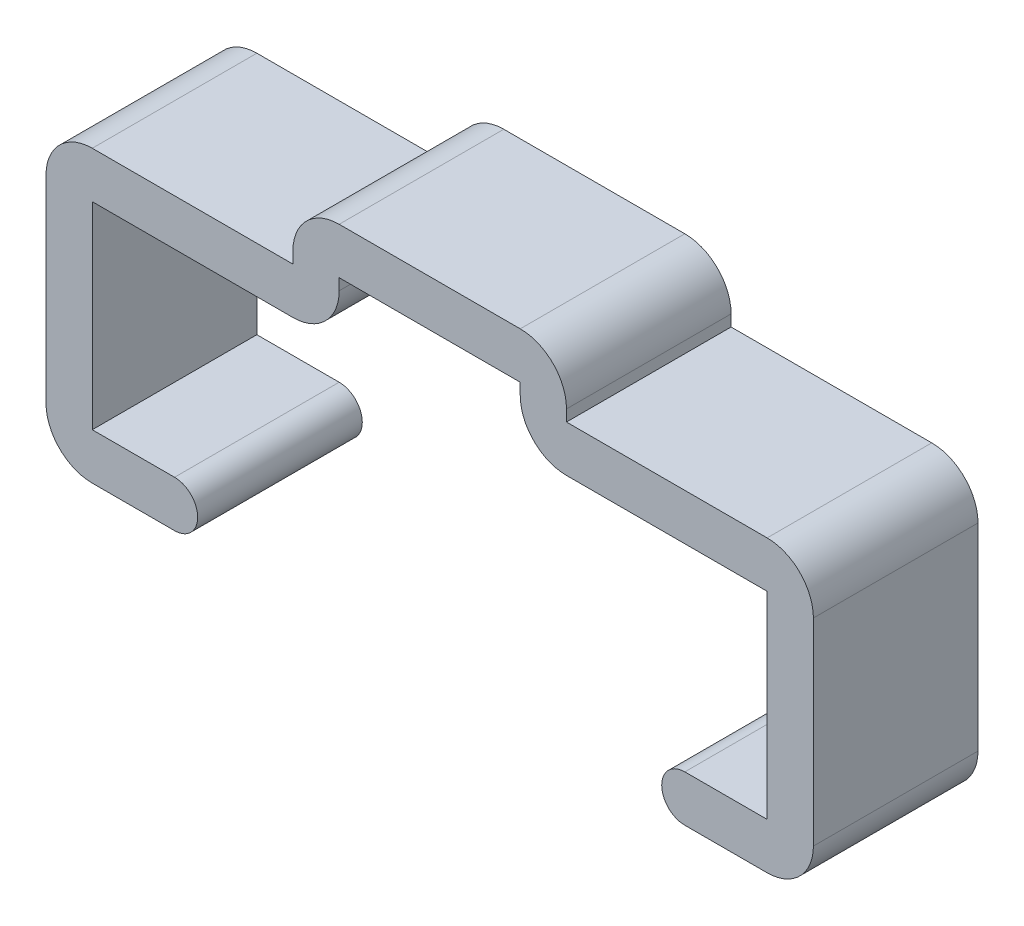
SolidWorks part; units mm, degrees
ref_plane "Front Plane" through (0, 0, 0) normal (0, 0, 1) x (1, 0, 0)
ref_plane "Top Plane" through (0, 0, 0) normal (0, 1, 0) x (1, 0, 0)
ref_plane "Right Plane" through (0, 0, 0) normal (1, 0, 0) x (0, 0, -1)
sketch "Sketch1" plane through (0, 0, 0) normal (0, 0, 1) x (1, 0, 0)
  line L0 (-20.5, -6) -> (-15.5, -6)
  line L1 (-20.5, 6) -> (-8.31, 6)
  line L2 (-20.5, 6) -> (-20.5, -6)
  line L4 (20.5, 6) -> (20.5, -6)
  line L5 (15.5, -6) -> (20.5, -6)
  line L6 (-20.5, -8.81) -> (-15.5, -8.81)
  line L7 (-5.5, 9.5) -> (5.5, 9.5)
  line L8 (-5.5, 9.5) -> (-5.5, 8.81)
  line L10 (5.5, 9.5) -> (5.5, 8.81)
  line L12 (-23.31, 6) -> (-23.31, -6)
  line L13 (-20.5, 8.81) -> (-8.31, 8.81)
  line L14 (-8.31, 8.81) -> (-8.31, 9.5)
  line L15 (-5.5, 12.31) -> (5.5, 12.31)
  line L16 (20.5, -8.81) -> (15.5, -8.81)
  line L17 (23.31, -6) -> (23.31, 6)
  line L18 (20.5, 8.81) -> (8.31, 8.81)
  line L19 (8.31, 8.81) -> (8.31, 9.5)
  line L20 (8.31, 6) -> (20.5, 6)
  arc A2 (-20.5, 8.81) -> (-23.31, 6) centre (-20.5, 6) ccw
  arc A3 (-23.31, -6) -> (-20.5, -8.81) centre (-20.5, -6) ccw
  arc A4 (-15.5, -8.81) -> (-15.5, -6) centre (-15.5, -7.405) ccw
  arc A5 (-8.31, 6) -> (-5.5, 8.81) centre (-8.31, 8.81) ccw
  arc A6 (-5.5, 12.31) -> (-8.31, 9.5) centre (-5.5, 9.5) ccw
  arc A7 (8.31, 9.5) -> (5.5, 12.31) centre (5.5, 9.5) ccw
  arc A8 (23.31, 6) -> (20.5, 8.81) centre (20.5, 6) ccw
  arc A9 (20.5, -8.81) -> (23.31, -6) centre (20.5, -6) ccw
  arc A10 (15.5, -6) -> (15.5, -8.81) centre (15.5, -7.405) ccw
  arc A11 (5.5, 8.81) -> (8.31, 6) centre (8.31, 8.81) ccw
extrude "Boss-Extrude1" add sketch "Sketch1" along normal blind 10
